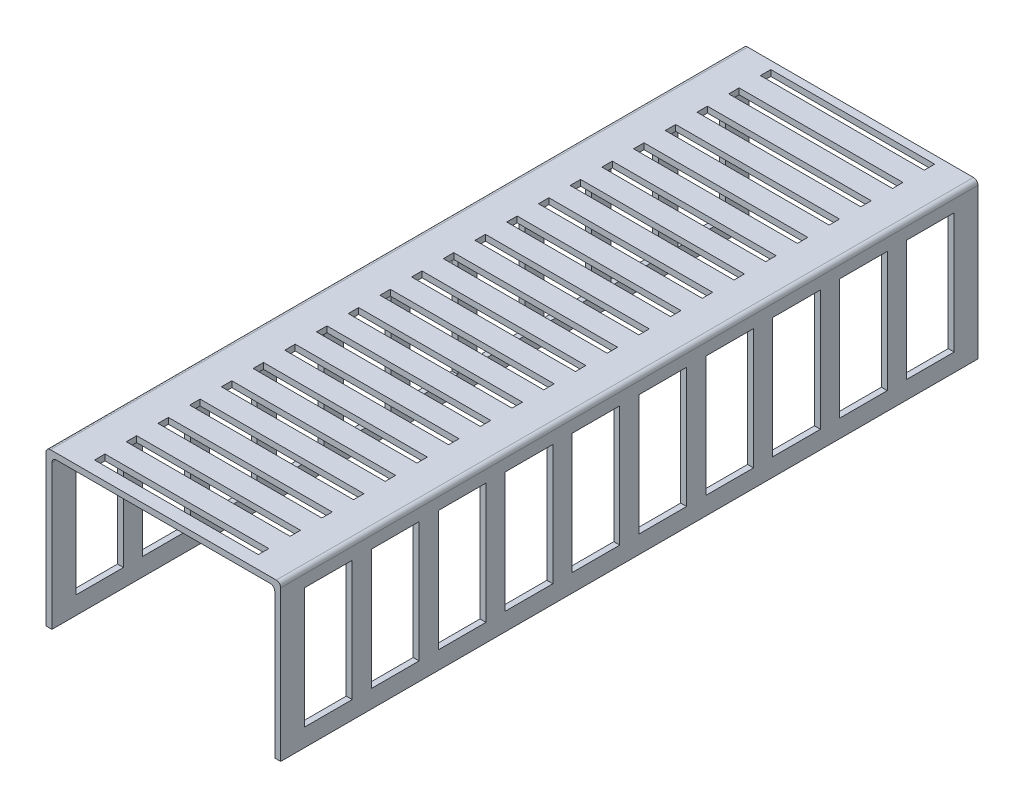
SolidWorks part; units mm, degrees
material "Nylon 101"
ref_plane "Front Plane" through (0, 0, 0) normal (0, 0, 1) x (1, 0, 0)
ref_plane "Top Plane" through (0, 0, 0) normal (0, 1, 0) x (1, 0, 0)
ref_plane "Right Plane" through (0, 0, 0) normal (1, 0, 0) x (0, 0, -1)
sketch "Sketch2" plane through (0, 26566.3493, 0) normal (0, 1, 0) x (1, 0, 0)
  line L0 (-34.7, 120.7548) -> (-34.7, 117.2548)
  line L5 (-34.7, 117.2548) -> (20.3, 117.2548)
  line L6 (-34.7, 120.7548) -> (20.3, 120.7548)
  line L7 (20.3, 120.7548) -> (20.3, 117.2548)
  line L9 (-46.6, 134.05) -> (32.2, 134.05)
  line L10 (-46.6, 134.05) -> (-46.6, -100.05)
  line L11 (-46.6, -100.05) -> (32.2, -100.05)
  line L12 (32.2, 134.05) -> (32.2, -100.05)
  line L13 (-49.2, -101.05) -> (34.8, -101.05) construction
  line L17 (33.2179, 129.65) -> (30.05, 129.65) construction
  line L18 (30.05, 124.75) -> (30.05, 130.7) construction
  line L19 (-38.7, 139.3) -> (-38.7, 131.4) construction
  line L20 (-34.7, 131.4) -> (20.3, 131.4)
  line L21 (-34.7, 131.4) -> (-34.7, 127.9)
  line L22 (-34.7, 127.9) -> (20.3, 127.9)
  line L23 (20.3, 131.4) -> (20.3, 127.9)
  line L24 (-34.7, 131.4) -> (20.3, 127.9) construction
  line L25 (-34.7, 127.9) -> (20.3, 131.4) construction
  line L26 (-34.7, 110.1095) -> (-34.7, 106.6095)
  line L27 (-34.7, 106.6095) -> (20.3, 106.6095)
  line L28 (-34.7, 110.1095) -> (20.3, 110.1095)
  line L29 (20.3, 110.1095) -> (20.3, 106.6095)
  line L30 (-34.7, 99.4643) -> (-34.7, 95.9643)
  line L31 (-34.7, 95.9643) -> (20.3, 95.9643)
  line L32 (-34.7, 99.4643) -> (20.3, 99.4643)
  line L33 (20.3, 99.4643) -> (20.3, 95.9643)
  line L34 (-34.7, 88.819) -> (-34.7, 85.319)
  line L35 (-34.7, 85.319) -> (20.3, 85.319)
  line L36 (-34.7, 88.819) -> (20.3, 88.819)
  line L37 (20.3, 88.819) -> (20.3, 85.319)
  line L38 (-34.7, 78.1738) -> (-34.7, 74.6738)
  line L39 (-34.7, 74.6738) -> (20.3, 74.6738)
  line L40 (-34.7, 78.1738) -> (20.3, 78.1738)
  line L41 (20.3, 78.1738) -> (20.3, 74.6738)
  line L42 (-34.7, 67.5286) -> (-34.7, 64.0286)
  line L43 (-34.7, 64.0286) -> (20.3, 64.0286)
  line L44 (-34.7, 67.5286) -> (20.3, 67.5286)
  line L45 (20.3, 67.5286) -> (20.3, 64.0286)
  line L46 (-34.7, 56.8833) -> (-34.7, 53.3833)
  line L47 (-34.7, 53.3833) -> (20.3, 53.3833)
  line L48 (-34.7, 56.8833) -> (20.3, 56.8833)
  line L49 (20.3, 56.8833) -> (20.3, 53.3833)
  line L50 (-34.7, 46.2381) -> (-34.7, 42.7381)
  line L51 (-34.7, 42.7381) -> (20.3, 42.7381)
  line L52 (-34.7, 46.2381) -> (20.3, 46.2381)
  line L53 (20.3, 46.2381) -> (20.3, 42.7381)
  line L54 (-34.7, 35.5929) -> (-34.7, 32.0929)
  line L55 (-34.7, 32.0929) -> (20.3, 32.0929)
  line L56 (-34.7, 35.5929) -> (20.3, 35.5929)
  line L57 (20.3, 35.5929) -> (20.3, 32.0929)
  line L58 (-34.7, 24.9476) -> (-34.7, 21.4476)
  line L59 (-34.7, 21.4476) -> (20.3, 21.4476)
  line L60 (-34.7, 24.9476) -> (20.3, 24.9476)
  line L61 (20.3, 24.9476) -> (20.3, 21.4476)
  line L62 (-34.7, 14.3024) -> (-34.7, 10.8024)
  line L63 (-34.7, 10.8024) -> (20.3, 10.8024)
  line L64 (-34.7, 14.3024) -> (20.3, 14.3024)
  line L65 (20.3, 14.3024) -> (20.3, 10.8024)
  line L66 (-34.7, 3.6571) -> (-34.7, 0.1571)
  line L67 (-34.7, 0.1571) -> (20.3, 0.1571)
  line L68 (-34.7, 3.6571) -> (20.3, 3.6571)
  line L69 (20.3, 3.6571) -> (20.3, 0.1571)
  line L70 (-34.7, -6.9881) -> (-34.7, -10.4881)
  line L71 (-34.7, -10.4881) -> (20.3, -10.4881)
  line L72 (-34.7, -6.9881) -> (20.3, -6.9881)
  line L73 (20.3, -6.9881) -> (20.3, -10.4881)
  line L74 (-34.7, -17.6333) -> (-34.7, -21.1333)
  line L75 (-34.7, -21.1333) -> (20.3, -21.1333)
  line L76 (-34.7, -17.6333) -> (20.3, -17.6333)
  line L77 (20.3, -17.6333) -> (20.3, -21.1333)
  line L78 (-34.7, -28.2786) -> (-34.7, -31.7786)
  line L79 (-34.7, -31.7786) -> (20.3, -31.7786)
  line L80 (-34.7, -28.2786) -> (20.3, -28.2786)
  line L81 (20.3, -28.2786) -> (20.3, -31.7786)
  line L82 (-34.7, -38.9238) -> (-34.7, -42.4238)
  line L83 (-34.7, -42.4238) -> (20.3, -42.4238)
  line L84 (-34.7, -38.9238) -> (20.3, -38.9238)
  line L85 (20.3, -38.9238) -> (20.3, -42.4238)
  line L86 (-34.7, -49.569) -> (-34.7, -53.069)
  line L87 (-34.7, -53.069) -> (20.3, -53.069)
  line L88 (-34.7, -49.569) -> (20.3, -49.569)
  line L89 (20.3, -49.569) -> (20.3, -53.069)
  line L90 (-34.7, -60.2143) -> (-34.7, -63.7143)
  line L91 (-34.7, -63.7143) -> (20.3, -63.7143)
  line L92 (-34.7, -60.2143) -> (20.3, -60.2143)
  line L93 (20.3, -60.2143) -> (20.3, -63.7143)
  line L94 (-34.7, -70.8595) -> (-34.7, -74.3595)
  line L95 (-34.7, -74.3595) -> (20.3, -74.3595)
  line L96 (-34.7, -70.8595) -> (20.3, -70.8595)
  line L97 (20.3, -70.8595) -> (20.3, -74.3595)
  line L98 (-34.7, -81.5048) -> (-34.7, -85.0048)
  line L99 (-34.7, -85.0048) -> (20.3, -85.0048)
  line L100 (-34.7, -81.5048) -> (20.3, -81.5048)
  line L101 (20.3, -81.5048) -> (20.3, -85.0048)
  line L102 (-34.7, -92.15) -> (-34.7, -95.65)
  line L103 (-34.7, -95.65) -> (20.3, -95.65)
  line L104 (-34.7, -92.15) -> (20.3, -92.15)
  line L105 (20.3, -92.15) -> (20.3, -95.65)
  line L107 (-49.2, 135.05) -> (34.8, 135.05) construction
  line L108 (-47.2, -100.65) -> (-47.2, 134.65) construction
  line L109 (32.8, -100.65) -> (32.8, 134.65) construction
  point P21 (-7.2, 129.65)
  dimension "D1" = 1
  dimension "D2" = 1
  dimension "D3" = 0.6
  dimension "D4" = 0.6
  dimension "D5" = 4
  dimension "D6" = 3.5
  dimension "D8" = 4.4
  dimension "D9" = 4.4
  dimension "D7" = 22
extrude "Boss-Extrude1" add sketch "Sketch2" along normal blind 2
sketch "Sketch3" plane through (0, 26566.3493, 0) normal (0, -1, 0) x (1, 0, 0)
  line L0 (32.2, -134.05) -> (-46.6, -134.05) construction
  line L1 (-46.6, 100.05) -> (-44.6, 100.05)
  line L2 (-46.6, 100.05) -> (-46.6, -134.05)
  line L3 (-46.6, -134.05) -> (-44.6, -134.05)
  line L4 (-44.6, 100.05) -> (-44.6, -134.05)
  line L5 (-7.2, 100.05) -> (-7.2, -2.7153) construction
  line L6 (-46.6, 100.05) -> (32.2, 100.05) construction
  line L7 (30.2, 100.05) -> (30.2, -134.05)
  line L8 (32.2, -134.05) -> (30.2, -134.05)
  line L9 (32.2, 100.05) -> (32.2, -134.05)
  line L10 (32.2, 100.05) -> (30.2, 100.05)
  dimension "D1" = 2
extrude "Boss-Extrude2" add sketch "Sketch3" along normal blind 50
fillet "Fillet1" radius 1.5 4 edges at (-44.6, 26566.3493, -17) (-46.6, 26568.3493, -17) (30.2, 26566.3493, -17) (32.2, 26568.3493, -17)
sketch "Sketch4" plane through (32.2, 0, 0) normal (1, 0, 0) x (0, 0, -1)
  line L0 (-100.05, 26566.8493) -> (-100.05, 26516.3493) construction
  line L1 (-92.05, 26562.8493) -> (-76.05, 26562.8493)
  line L2 (-92.05, 26562.8493) -> (-92.05, 26522.3493)
  line L3 (-92.05, 26522.3493) -> (-76.05, 26522.3493)
  line L4 (-76.05, 26562.8493) -> (-76.05, 26522.3493)
  line L5 (134.05, 26566.8493) -> (-100.05, 26566.8493) construction
  line L6 (134.05, 26516.3493) -> (-100.05, 26516.3493) construction
  line L7 (-69.5944, 26562.8493) -> (-53.5944, 26562.8493)
  line L8 (-69.5944, 26562.8493) -> (-69.5944, 26522.3493)
  line L9 (-69.5944, 26522.3493) -> (-53.5944, 26522.3493)
  line L10 (-53.5944, 26562.8493) -> (-53.5944, 26522.3493)
  line L11 (-47.1389, 26562.8493) -> (-31.1389, 26562.8493)
  line L12 (-47.1389, 26562.8493) -> (-47.1389, 26522.3493)
  line L13 (-47.1389, 26522.3493) -> (-31.1389, 26522.3493)
  line L14 (-31.1389, 26562.8493) -> (-31.1389, 26522.3493)
  line L15 (-24.6833, 26562.8493) -> (-8.6833, 26562.8493)
  line L16 (-24.6833, 26562.8493) -> (-24.6833, 26522.3493)
  line L17 (-24.6833, 26522.3493) -> (-8.6833, 26522.3493)
  line L18 (-8.6833, 26562.8493) -> (-8.6833, 26522.3493)
  line L19 (-2.2278, 26562.8493) -> (13.7722, 26562.8493)
  line L20 (-2.2278, 26562.8493) -> (-2.2278, 26522.3493)
  line L21 (-2.2278, 26522.3493) -> (13.7722, 26522.3493)
  line L22 (13.7722, 26562.8493) -> (13.7722, 26522.3493)
  line L23 (20.2278, 26562.8493) -> (36.2278, 26562.8493)
  line L24 (20.2278, 26562.8493) -> (20.2278, 26522.3493)
  line L25 (20.2278, 26522.3493) -> (36.2278, 26522.3493)
  line L26 (36.2278, 26562.8493) -> (36.2278, 26522.3493)
  line L27 (42.6833, 26562.8493) -> (58.6833, 26562.8493)
  line L28 (42.6833, 26562.8493) -> (42.6833, 26522.3493)
  line L29 (42.6833, 26522.3493) -> (58.6833, 26522.3493)
  line L30 (58.6833, 26562.8493) -> (58.6833, 26522.3493)
  line L31 (65.1389, 26562.8493) -> (81.1389, 26562.8493)
  line L32 (65.1389, 26562.8493) -> (65.1389, 26522.3493)
  line L33 (65.1389, 26522.3493) -> (81.1389, 26522.3493)
  line L34 (81.1389, 26562.8493) -> (81.1389, 26522.3493)
  line L35 (87.5944, 26562.8493) -> (103.5944, 26562.8493)
  line L36 (87.5944, 26562.8493) -> (87.5944, 26522.3493)
  line L37 (87.5944, 26522.3493) -> (103.5944, 26522.3493)
  line L38 (103.5944, 26562.8493) -> (103.5944, 26522.3493)
  line L39 (110.05, 26562.8493) -> (126.05, 26562.8493)
  line L40 (110.05, 26562.8493) -> (110.05, 26522.3493)
  line L41 (110.05, 26522.3493) -> (126.05, 26522.3493)
  line L42 (126.05, 26562.8493) -> (126.05, 26522.3493)
  line L43 (134.05, 26566.8493) -> (134.05, 26516.3493) construction
  dimension "D1" = 8
  dimension "D2" = 4
  dimension "D3" = 6
  dimension "D4" = 16
  dimension "D6" = 8
  dimension "D5" = 10
extrude "Cut-Extrude1" cut sketch "Sketch4" against normal through all
